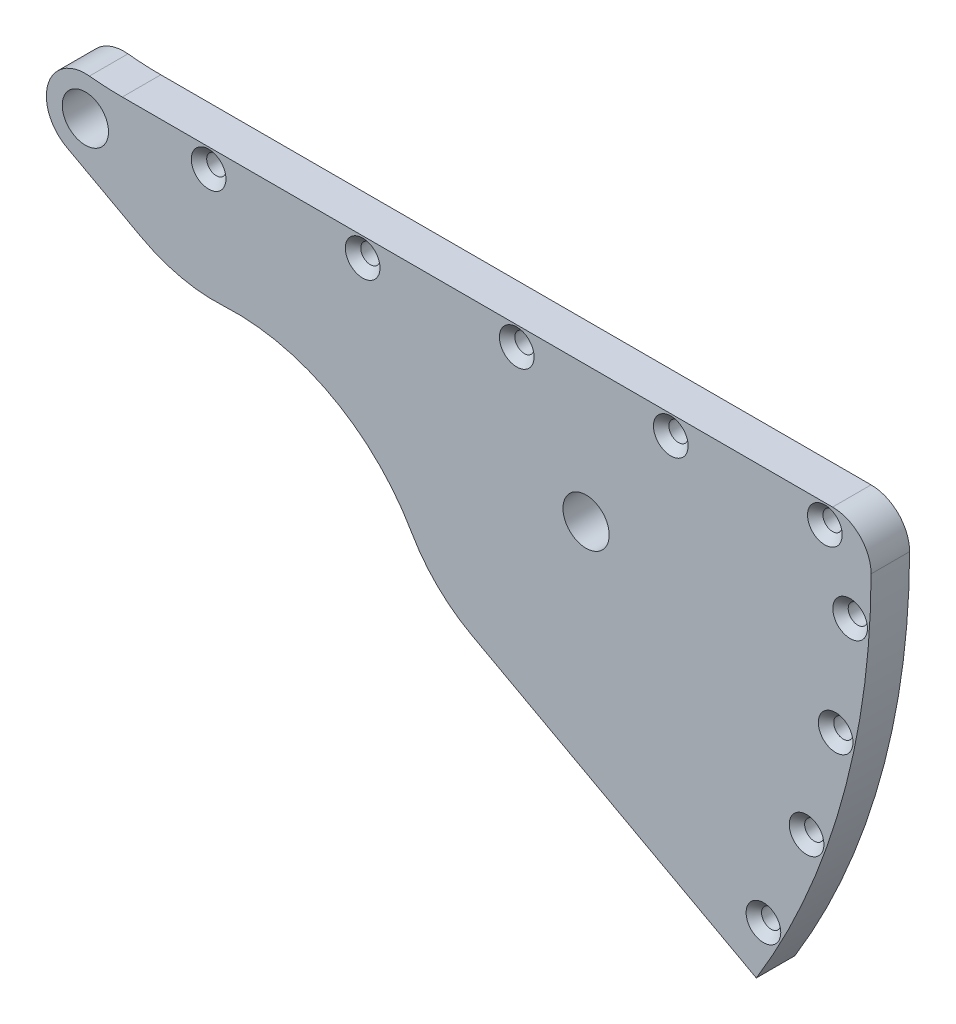
SolidWorks part; units mm, degrees
ref_plane "Front Plane" through (0, 0, 0) normal (0, 0, 1) x (1, 0, 0)
ref_plane "Top Plane" through (0, 0, 0) normal (0, 1, 0) x (1, 0, 0)
ref_plane "Right Plane" through (0, 0, 0) normal (1, 0, 0) x (0, 0, -1)
sketch "Sketch1" plane through (0, 0, 0) normal (0, 0, 1) x (1, 0, 0)
  line L3 (134, -12.3683) -> (134, -2.7366)
  line L4 (134, -2.7366) -> (-66.8565, -2.7366)
  line L5 (-74.8359, -21.2714) -> (104.2053, -118.5215)
  line L6 (134, -12.3683) -> (134, -2.7366)
  line L7 (134, -2.7366) -> (-66.8565, -2.7366)
  line L8 (-74.8359, -21.2714) -> (104.2053, -118.5215)
  circle A0 centre (60, -38) radius 3 construction
  circle A1 centre (60, -38) radius 3
  circle A2 centre (-70, -12.3683) radius 3 construction
  circle A3 centre (-70, -12.3683) radius 3
  arc A4 (130.3667, -50.6984) -> (132.3833, -38) centre (-70, -12.3683) ccw
  arc A5 (132.3833, -38) -> (134, -12.3683) centre (-70, -12.3683) ccw
  arc A6 (-66.8565, -2.7366) -> (-74.8359, -21.2714) centre (-70, -12.3683) ccw
  arc A7 (104.2053, -118.5215) -> (130.3667, -50.6984) centre (-70, -12.3683) ccw
  arc A8 (130.3667, -50.6984) -> (132.3833, -38) centre (-70, -12.3683) ccw
  arc A9 (132.3833, -38) -> (134, -12.3683) centre (-70, -12.3683) ccw
  arc A10 (-66.8565, -2.7366) -> (-74.8359, -21.2714) centre (-70, -12.3683) ccw
  arc A11 (104.2053, -118.5215) -> (130.3667, -50.6984) centre (-70, -12.3683) ccw
  dimension "D1" = 0
extrude "Boss-Extrude1" add sketch "Sketch1" along normal blind 10
sketch "Sketch2" plane through (0, 0, 10) normal (0, 0, 1) x (1, 0, 0)
  circle A0 centre (60, -38) radius 6
  circle A2 centre (-70, -12.3683) radius 6
  dimension "D1" = 12
  dimension "D2" = 12
extrude "Cut-Extrude1" cut sketch "Sketch2" against normal blind 10
sketch "Sketch3" plane through (0, 0, 10) normal (0, 0, 1) x (1, 0, 0)
  circle A0 centre (-31.102, -89.2099) radius 52.7281
  point P2 (-27.9752, -85.6661)
  point P3 (-31.102, -89.2099)
extrude "Cut-Extrude2" cut sketch "Sketch3" against normal blind 10
fillet "Fillet1" radius 40 2 edges at (18.7801, -72.1209, 5) (-43.9207, -38.0637, 5)
sketch "Sketch4" plane through (0, 0, 10) normal (0, 0, 1) x (1, 0, 0)
  circle A0 centre (122, -7.7366) radius 2.5
  dimension "D2" = 5
extrude "Cut-Extrude3" cut sketch "Sketch4" against normal blind 10
chamfer "Chamfer1" distance 2 angle 45 1 edges at (124.5, -7.7366, 10)
fillet "Fillet2" radius 10 1 edges at (134, -2.7366, 5)
pattern_linear "LPattern3" count 5 spacing 40 along (-1, 0, 0) of "Cut-Extrude3", "Chamfer1"
sketch "Sketch5" plane through (0, 0, 10) normal (0, 0, 1) x (1, 0, 0)
  circle A6 centre (128.5655, -25.5108) radius 2.5
  dimension "D2" = 5
extrude "Cut-Extrude4" cut sketch "Sketch5" against normal blind 10
chamfer "Chamfer2" distance 2 angle 45 1 edges at (131.0655, -25.5108, 10)
pattern_circular "CirPattern2" count 45 over 360 about axis through (-70, -12.3683, 10) along (0, 0, 1) skipping 1, 2, 3, 4, 5, 6, 7, 8, 9, 10, 11, 12, 13, 14, 15, 16, 17, 18, 19, 20, 21, 22, 23, 24, 25, 26, 27, 28, 29, 30, 31, 32, 33, 34, 35, 36, 37, 38, 39, 40, 41 of "Chamfer2", "Cut-Extrude4"
fillet "Fillet4" radius 82 1 edges at (-66.8565, -2.7366, 5)
